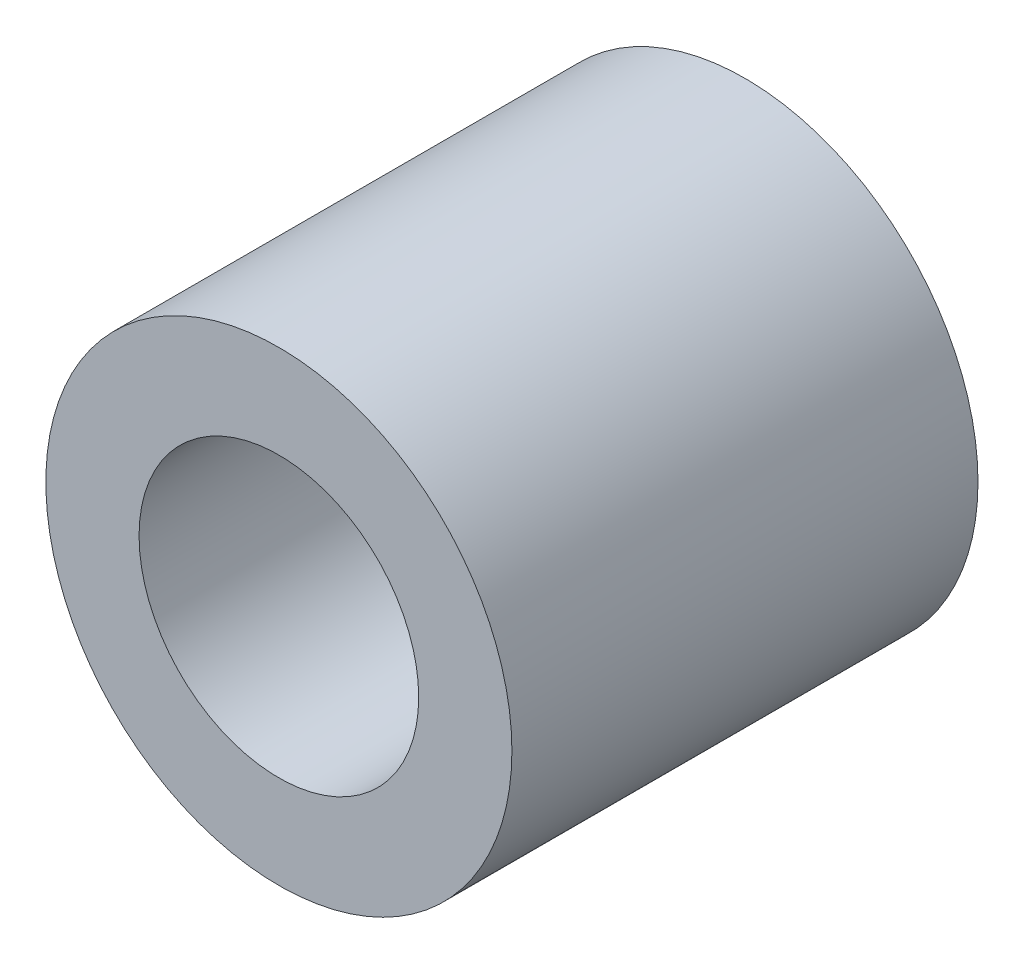
SolidWorks part; units mm, degrees
ref_plane "Front Plane" through (0, 0, 0) normal (0, 0, 1) x (1, 0, 0)
ref_plane "Top Plane" through (0, 0, 0) normal (0, 1, 0) x (1, 0, 0)
ref_plane "Right Plane" through (0, 0, 0) normal (1, 0, 0) x (0, 0, -1)
sketch "Sketch1" plane through (0, 0, 0) normal (0, 0, 1) x (1, 0, 0)
  circle A0 centre (0, 0) radius 3
  circle A1 centre (0, 0) radius 5
extrude "Boss-Extrude1" add sketch "Sketch1" along normal blind 10
